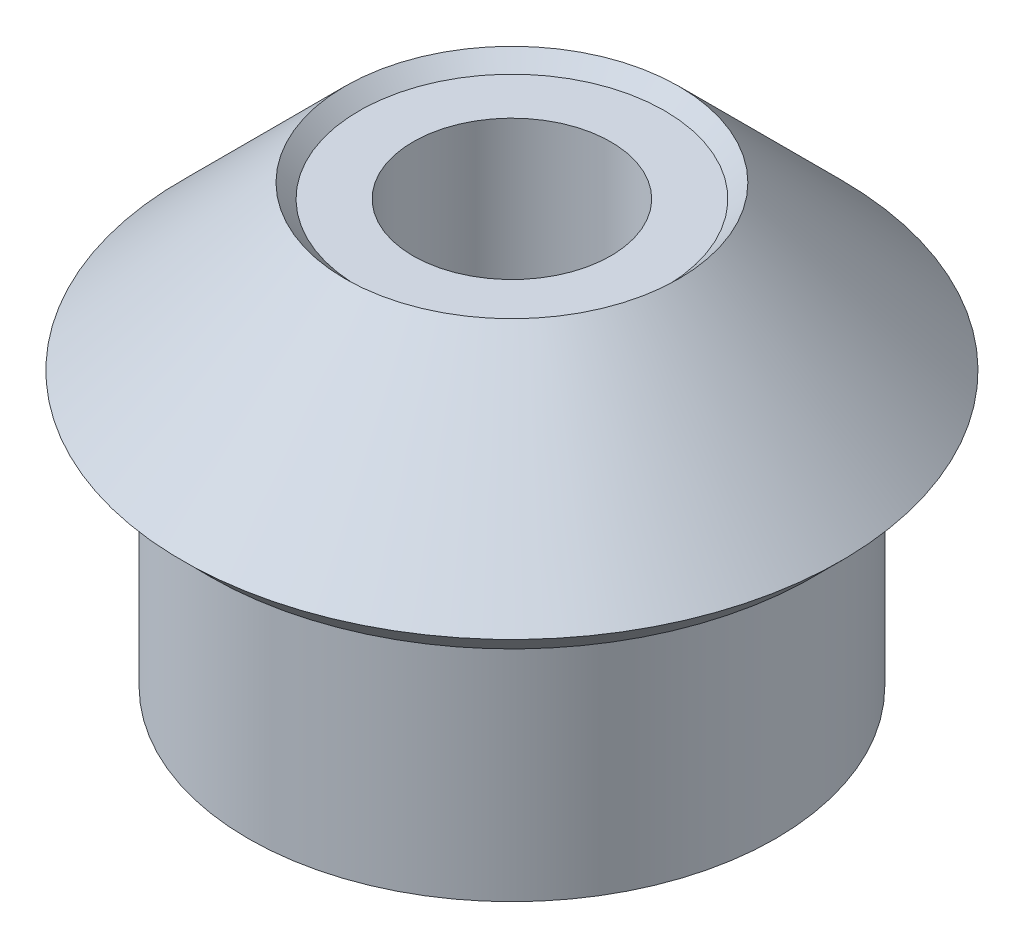
SolidWorks part; units mm, degrees
material "普通碳钢"
ref_plane "前视基准面" through (0, 0, 0) normal (0, 0, 1) x (1, 0, 0)
ref_plane "上视基准面" through (0, 0, 0) normal (0, 1, 0) x (1, 0, 0)
ref_plane "右视基准面" through (0, 0, 0) normal (1, 0, 0) x (0, 0, -1)
sketch "草图1" plane through (0, 0, 0) normal (0, 0, 1) x (1, 0, 0)
  line L0 (0, 0) -> (0, 18.4693) construction
  line L1 (0, 18.3046) -> (10.7071, 9.0117) construction
  line L2 (5.4206, 13.6) -> (10.7071, 9.0117) construction
  line L3 (10.7071, 9.0117) -> (9.1515, 7.4561) construction
  line L4 (9.1515, 7.4561) -> (8, 7.4561)
  line L5 (8, 7.4561) -> (8, 0)
  line L6 (8, 0) -> (0, 0)
  line L7 (0, 18.3046) -> (10, 8.3046) construction
  line L8 (5.4206, 13.6) -> (4.633, 12.8124) construction
  line L9 (0, 12.8124) -> (4.633, 12.8124)
  line L10 (0, 12.8124) -> (0, 0)
  line L11 (0, 18.3046) -> (9.1515, 7.4561) construction
  line L12 (4.633, 12.8124) -> (5.0626, 13.242)
  line L13 (5.0626, 13.242) -> (10, 8.3046)
  line L14 (10, 8.3046) -> (9.1515, 7.4561)
  dimension "D1" = 7
  dimension "D2" = 45
  dimension "D3" = 10
  dimension "D4" = 8
  dimension "D5" = 1
  dimension "D6" = 13.6
  dimension "D9" = 2.2
revolve "旋转1" add sketch "草图1" angle 360 about L0
sketch "草图3" plane through (0, 12.8124, 0) normal (0, 1, 0) x (1, 0, 0)
  circle A0 centre (0, 0) radius 3
  dimension "D1" = 6
extrude "切除-拉伸1" cut sketch "草图3" against normal through all
ref_point "点1"
